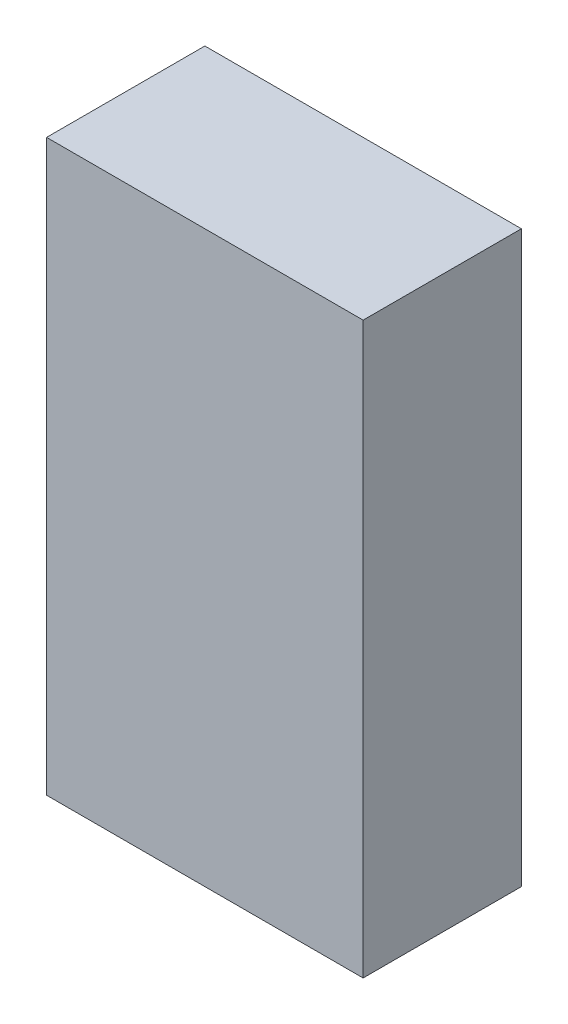
SolidWorks part; units mm, degrees
ref_plane "Front Plane" through (0, 0, 0) normal (0, 0, 1) x (1, 0, 0)
ref_plane "Top Plane" through (0, 0, 0) normal (0, 1, 0) x (1, 0, 0)
ref_plane "Right Plane" through (0, 0, 0) normal (1, 0, 0) x (0, 0, -1)
sketch "Sketch1" plane through (0, 0, 0) normal (0, 0, 1) x (1, 0, 0)
  line L1 (-5, 9) -> (5, 9)
  line L2 (-5, 9) -> (-5, -9)
  line L3 (-5, -9) -> (5, -9)
  line L4 (5, 9) -> (5, -9)
  line L5 (-5, 9) -> (5, -9) construction
  line L6 (-5, -9) -> (5, 9) construction
  point P0 (0, 0)
  dimension "D1" = 18
  dimension "D2" = 10
extrude "Boss-Extrude1" add sketch "Sketch1" along normal blind 5
